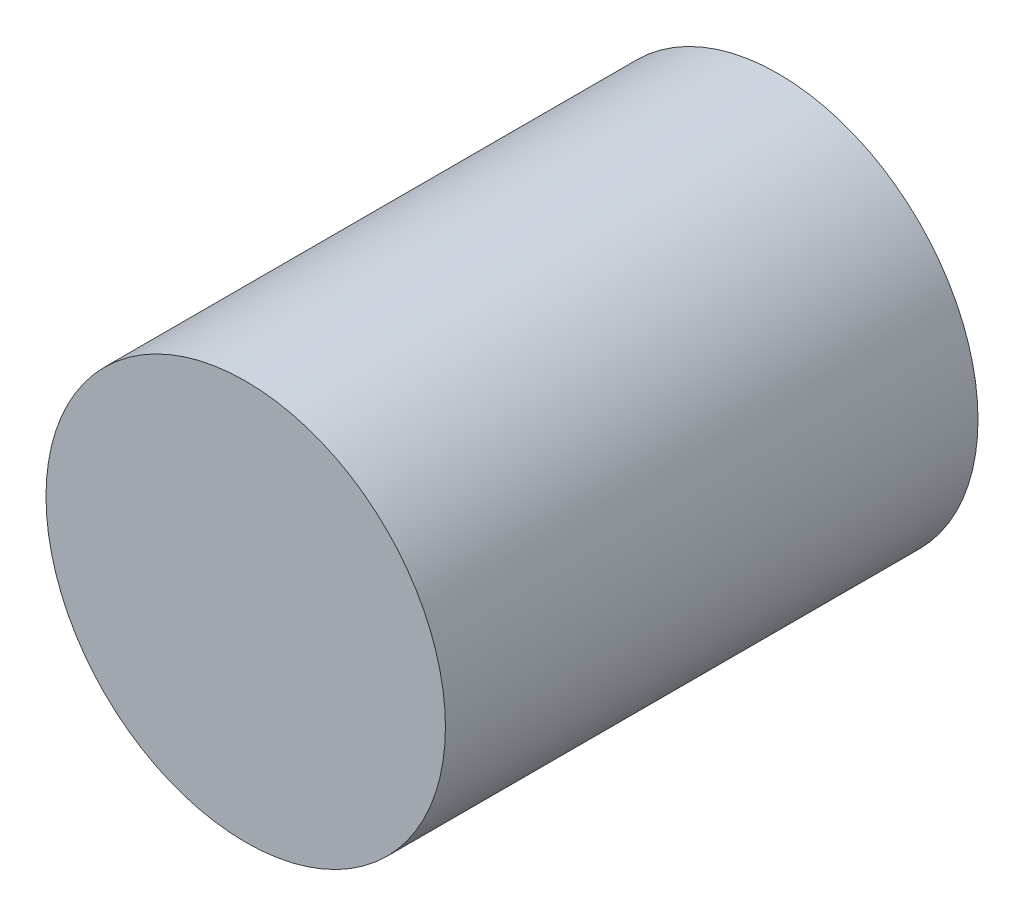
SolidWorks part; units mm, degrees
ref_plane "Front Plane" through (0, 0, 0) normal (0, 0, 1) x (1, 0, 0)
ref_plane "Top Plane" through (0, 0, 0) normal (0, 1, 0) x (1, 0, 0)
ref_plane "Right Plane" through (0, 0, 0) normal (1, 0, 0) x (0, 0, -1)
sketch "Sketch1" plane through (0, 0, 0) normal (0, 0, 1) x (1, 0, 0)
  circle A0 centre (0, 0) radius 15
  dimension "D1" = 30
extrude "Boss-Extrude1" add sketch "Sketch1" along normal blind 40
sketch "Sketch3" plane through (0, 0, 40) normal (0, 0, 1) x (1, 0, 0)
  line L0 (0, 15) -> (0, -15) construction
  circle A0 centre (0, 0) radius 15 construction
